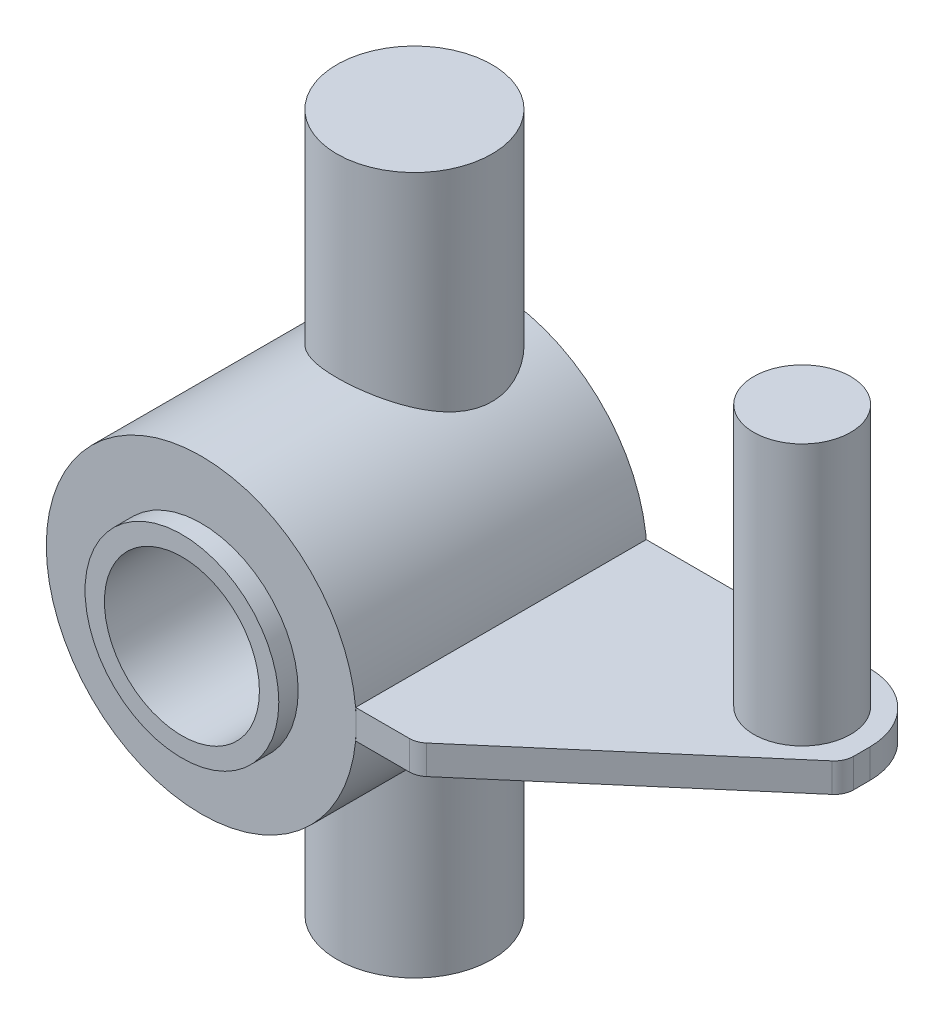
SolidWorks part; units mm, degrees
ref_plane "Front Plane" through (0, 0, 0) normal (0, 0, 1) x (1, 0, 0)
ref_plane "Top Plane" through (0, 0, 0) normal (0, 1, 0) x (1, 0, 0)
ref_plane "Right Plane" through (0, 0, 0) normal (1, 0, 0) x (0, 0, -1)
sketch "Sketch1" plane through (0, 0, 0) normal (0, 0, 1) x (1, 0, 0)
  line L0 (8.8, 8) -> (-8.8, 8) construction
  line L1 (8.8, 0) -> (-8.8, 0) construction
  circle A0 centre (0, 0) radius 8
  dimension "D1" = 16
extrude "Boss-Extrude1" add sketch "Sketch1" along normal blind 15
sketch "Sketch2" plane through (0, 0, 15) normal (0, 0, 1) x (1, 0, 0)
  circle A0 centre (0, 0) radius 5
  circle A1 centre (0, 0) radius 4
  dimension "D1" = 10
  dimension "D2" = 8
extrude "Boss-Extrude2" add sketch "Sketch2" along normal blind 1 contours A0
sketch "Sketch3" plane through (0, 0, 15) normal (0, 0, 1) x (1, 0, 0)
  circle A1 centre (0, 0) radius 4
  circle A2 centre (0, 0) radius 4
  dimension "D1" = 0
extrude "Cut-Extrude1" cut sketch "Sketch3" against normal blind 15
ref_plane "Plane1" through (0, 8, 0) normal (0, 1, 0) x (1, 0, 0)
sketch "Sketch4" plane through (0, 8, 0) normal (0, 1, 0) x (1, 0, 0)
  circle A5 centre (0, -4) radius 4
  dimension "D1" = 8
  dimension "D2" = 4
extrude "Boss-Extrude3" add sketch "Sketch4" along normal blind 10 and the other way up to surface separate body other way up to face at (8, 0, 15)
ref_plane "Plane2" through (0, -8, 0) normal (0, -1, 0) x (-1, 0, 0)
sketch "Sketch6" plane through (0, -8, 0) normal (0, -1, 0) x (-1, 0, 0)
  circle A0 centre (0, -4) radius 4
  dimension "D1" = 4
  dimension "D2" = 8
extrude "Boss-Extrude4" add sketch "Sketch6" along normal blind 10 and the other way up to surface other way up to face at (8, 0, 15)
ref_plane "Plane3" through (8, 0, 0) normal (1, 0, 0) x (0, 0, -1)
sketch "Sketch7" plane through (8, 0, 0) normal (1, 0, 0) x (0, 0, -1)
  line L9 (0, -0.75) -> (-15, -0.75)
  line L10 (0, -0.75) -> (0, 0.75)
  line L11 (0, 0.75) -> (-15, 0.75)
  line L12 (-15, -0.75) -> (-15, 0.75)
  point P4 (0, 0)
  dimension "D1" = 15
  dimension "D2" = 1.5
extrude "Boss-Extrude5" add sketch "Sketch7" along normal blind 15 and the other way up to surface separate body other way up to face at (8, 0, 15)
sketch "Sketch9" plane through (0, -0.75, 0) normal (0, -1, 0) x (1, 0, 0)
  line L4 (7.9648, 15) -> (7.9648, 0)
  line L5 (7.9648, 0) -> (23, 0)
  line L6 (23, 0) -> (23, 15)
  line L7 (23, 15) -> (7.9648, 15)
  line L9 (7.9648, 0) -> (23, 0)
  line L10 (23, 0) -> (23, 15)
  line L11 (23, 15) -> (7.9648, 15)
  line L12 (7.9648, 15) -> (7.9648, 0)
  circle A0 centre (19.5, 3.5) radius 3.5
  line M8 (23, 0) -> (23, 15)
  dimension "D1" = 0
  dimension "D2" = 7
extrude "Cut-Extrude2" cut sketch "Sketch9" against normal blind 15 contours A0 L9 M8
sketch "Sketch11" plane through (0, -0.75, 0) normal (0, -1, 0) x (-1, 0, 0)
  line L0 (-11.1081, -15) -> (-23, -4.7928) construction
  line L1 (-23, -15) -> (-7.9648, -15) construction
  line L2 (-23, -15) -> (-23, -3.5) construction
  line M3 (-23, -3.5) -> (-23, -15)
  line M4 (-23, -15) -> (-7.9648, -15)
extrude "Cut-Extrude3" cut sketch "Sketch11" against normal blind 15 contours L0 M4 M3
fillet "Fillet1" radius 1 1 edges at (11.1081, 0, 15)
fillet "Fillet2" radius 1 1 edges at (23, 0, 4.7928)
sketch "Sketch12" plane through (0, -0.75, 0) normal (0, -1, 0) x (1, 0, 0)
  arc A2 (19.5, 0) -> (23, 3.5) centre (19.5, 3.5) ccw construction
  arc A3 (19.5, 0) -> (23, 3.5) centre (19.5, 3.5) ccw
  circle A4 centre (19.4463, 3.435) radius 2.5
  point P1 (21.9749, 1.0251)
  dimension "D1" = 5
  dimension "D3" = 2.5286
  dimension "D2" = 3.435
sketch "Sketch13" plane through (0, 0, 0) normal (0, 1, 0) x (1, 0, 0)
  line L0 (0, 0) -> (0, -16.3088) construction
extrude "Boss-Extrude6" add sketch "Sketch12" against normal blind 15 contours A4
